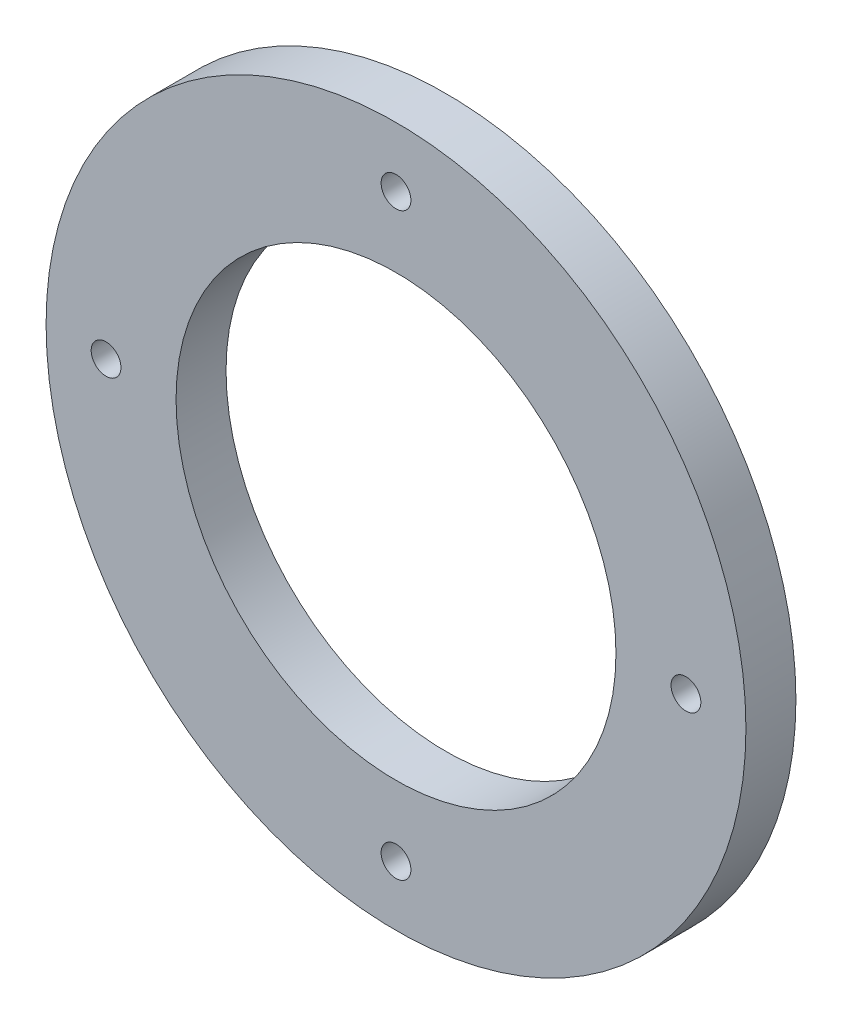
SolidWorks part; units mm, degrees
ref_plane "Front Plane" through (0, 0, 0) normal (0, 0, 1) x (1, 0, 0)
ref_plane "Top Plane" through (0, 0, 0) normal (0, 1, 0) x (1, 0, 0)
ref_plane "Right Plane" through (0, 0, 0) normal (1, 0, 0) x (0, 0, -1)
sketch "Sketch1" plane through (0, 0, 0) normal (0, 0, 1) x (1, 0, 0)
  circle A0 centre (0, 0) radius 35
  circle A1 centre (0, 0) radius 22
  circle A3 centre (29, 0) radius 1.49
  circle A4 centre (0, 29) radius 1.49
  circle A5 centre (-29, 0) radius 1.49
  circle A6 centre (0, -29) radius 1.49
  dimension "D1" = 70
  dimension "D2" = 44
  dimension "D3" = 2.98
  dimension "D4" = 2.98
  dimension "D5" = 2.98
  dimension "D6" = 2.98
extrude "Boss-Extrude1" add sketch "Sketch1" along normal blind 5
